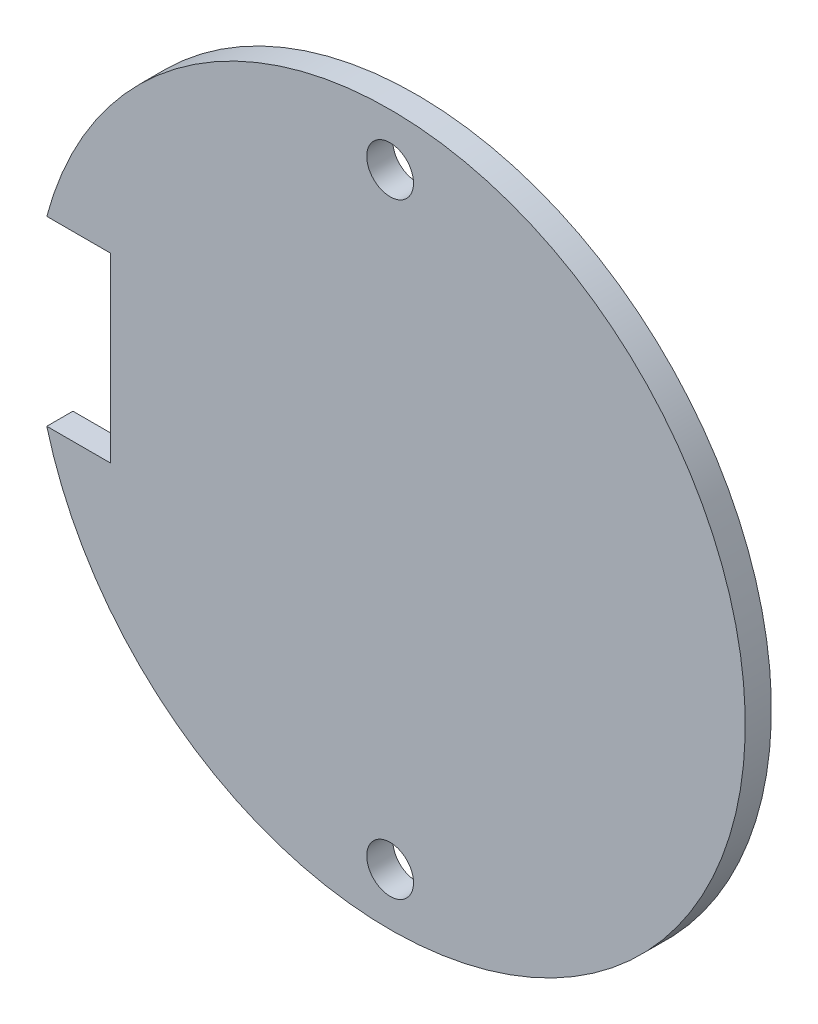
SolidWorks part; units mm, degrees
ref_plane "Front Plane" through (0, 0, 0) normal (0, 0, 1) x (1, 0, 0)
ref_plane "Top Plane" through (0, 0, 0) normal (0, 1, 0) x (1, 0, 0)
ref_plane "Right Plane" through (0, 0, 0) normal (1, 0, 0) x (0, 0, -1)
sketch "Sketch1" plane through (0, 0, 0) normal (0, 0, 1) x (1, 0, 0)
  line L0 (-20.8712, 5.5245) -> (-16.9841, 5.5245) construction
  line L1 (-16.9841, 5.5245) -> (-16.9841, -5.5245) construction
  line L2 (-16.9841, -5.5245) -> (-20.8712, -5.5245) construction
  line L3 (-20.8712, 5.5245) -> (-16.9841, 5.5245)
  line L4 (-16.9841, 5.5245) -> (-16.9841, -5.5245)
  line L5 (-16.9841, -5.5245) -> (-20.8712, -5.5245)
  circle A0 centre (0, 18.415) radius 1.4224 construction
  circle A1 centre (0, -18.415) radius 1.4224 construction
  circle A2 centre (0, 18.415) radius 1.4224
  circle A3 centre (0, -18.415) radius 1.4224
  arc A4 (-20.8712, -5.5245) -> (-20.8712, 5.5245) centre (0, 0) ccw
extrude "Boss-Extrude1" add sketch "Sketch1" along normal blind 1.5875
